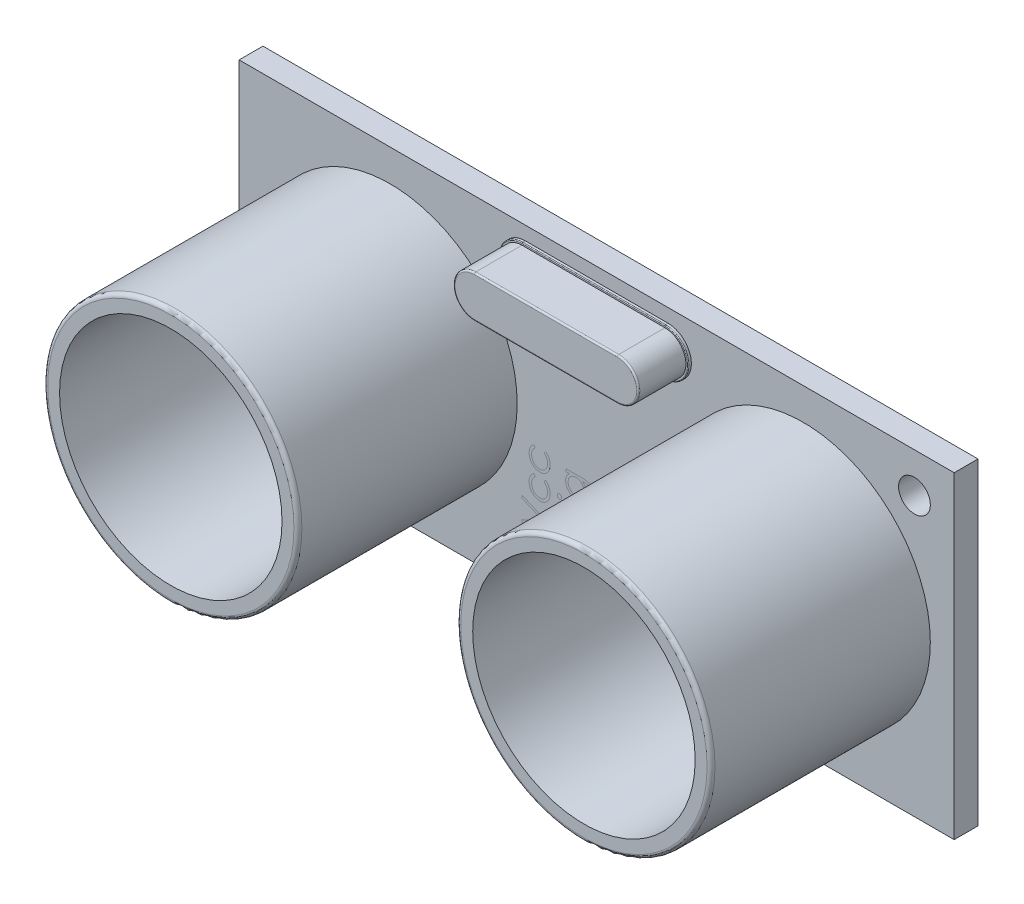
SolidWorks part; units mm, degrees
ref_plane "Front Plane" through (0, 0, 0) normal (0, 0, 1) x (1, 0, 0)
ref_plane "Top Plane" through (0, 0, 0) normal (0, 1, 0) x (1, 0, 0)
ref_plane "Right Plane" through (0, 0, 0) normal (1, 0, 0) x (0, 0, -1)
sketch "Sketch1" plane through (0, 0, 0) normal (0, 0, 1) x (1, 0, 0)
  line L1 (0, 0) -> (45, 0)
  line L2 (0, 0) -> (0, 20)
  line L3 (0, 20) -> (45, 20)
  line L4 (45, 0) -> (45, 20)
  circle A0 centre (2.5, 2.5) radius 1
  circle A1 centre (42.5, 17.5) radius 1
  dimension "D3" = 2
  dimension "D4" = 2
  dimension "D5" = 15
  dimension "D6" = 2.5
  dimension "D7" = 2.5
  dimension "D8" = 40
  dimension "D1" = 20
  dimension "D2" = 45
extrude "Boss-Extrude1" add sketch "Sketch1" along normal blind 1.5
sketch "Sketch2" plane through (0, 0, 1.5) normal (0, 0, 1) x (1, 0, 0)
  line L1 (45, 20) -> (0, 20) construction
  line L2 (22.5, 0) -> (22.5, 20) construction
  line L3 (0, 0) -> (45, 0) construction
  line L4 (22.5, 20) -> (22.5, 10) construction
  line L5 (22.5, 10) -> (35.5, 10) construction
  circle A0 centre (9.5, 10) radius 8
  circle A1 centre (35.5, 10) radius 8
  dimension "D1" = 16
  dimension "D2" = 16
  dimension "D3" = 13
  dimension "D5" = 10
  dimension "D6" = 10
  dimension "D7" = 13
extrude "Boss-Extrude2" add sketch "Sketch2" along normal blind 13.8
sketch "Sketch3" plane through (0, 0, 15.3) normal (0, 0, 1) x (1, 0, 0)
  circle A0 centre (9.5, 10) radius 7
  circle A1 centre (35.5, 10) radius 7
  circle A2 centre (35.5, 10) radius 8 construction
  dimension "D1" = 14
  dimension "D2" = 14
  dimension "D3" = 0
extrude "Cut-Extrude1" cut sketch "Sketch3" against normal blind 11
sketch "Sketch4" plane through (0, 0, 4.3) normal (0, 0, 1) x (1, 0, 0)
  circle A0 centre (9.5, 10) radius 6
  circle A1 centre (35.5, 10) radius 6
  circle A2 centre (35.5, 10) radius 7 construction
  dimension "D1" = 12
  dimension "D2" = 12
  dimension "D3" = 0
extrude "Boss-Extrude3" add sketch "Sketch4" along normal blind 1
fillet "Fillet1" radius 0.25 2 edges at (43.5, 10, 15.3) (17.5, 10, 15.3)
sketch "Sketch6" plane through (0, 0, 1.5) normal (0, 0, 1) x (1, 0, 0)
  line L0 (18.0118, 17.6702) -> (26.9882, 17.6702) construction
  line L1 (18.0118, 19.1439) -> (26.9882, 19.1439)
  line L2 (18.0118, 16.1964) -> (26.9882, 16.1964)
  line L3 (22.5, 20) -> (22.5, 17.6702) construction
  line L4 (45, 20) -> (0, 20) construction
  arc A0 (18.0118, 19.1439) -> (18.0118, 16.1964) centre (18.0118, 17.6702) ccw
  arc A1 (26.9882, 16.1964) -> (26.9882, 19.1439) centre (26.9882, 17.6702) ccw
  point P2 (22.5, 17.6702)
extrude "Boss-Extrude4" add sketch "Sketch6" along normal blind 0.2
sketch "Sketch7" plane through (0, 0, 1.7) normal (0, 0, 1) x (1, 0, 0)
  line L0 (18.001, 17.6795) -> (26.999, 17.6795) construction
  line L1 (18.001, 18.9989) -> (26.999, 18.9989)
  line L2 (18.001, 16.3602) -> (26.999, 16.3602)
  line L3 (0, 0) -> (45, 0) construction
  line L4 (45, 0) -> (22.5, 0) construction
  line L5 (22.5, 0) -> (22.5, 21.8843) construction
  arc A0 (18.001, 18.9989) -> (18.001, 16.3602) centre (18.001, 17.6795) ccw
  arc A1 (26.999, 16.3602) -> (26.999, 18.9989) centre (26.999, 17.6795) ccw
  point P2 (22.5, 17.6795)
  point P11 (22.5, 17.6795)
extrude "Boss-Extrude5" add sketch "Sketch7" along normal blind 3
fillet "Fillet2" radius 0.1 4 edges at (16.6817, 17.6795, 4.7) (22.5, 18.9989, 4.7) (28.3183, 17.6795, 4.7) (22.5, 16.3602, 4.7)
fillet "Fillet3" radius 0.05 4 edges at (28.462, 17.6702, 1.7) (22.5, 16.1964, 1.7) (16.538, 17.6702, 1.7) (22.5, 19.1439, 1.7)
sketch "Sketch9" plane through (0, 0, 0) normal (0, 0, -1) x (-1, 0, 0)
  line L1 (0, 0) -> (-45, 0) construction
  circle A0 centre (-26.31, 2.5) radius 0.635
  circle A1 centre (-23.77, 2.5) radius 0.635
  circle A2 centre (-21.23, 2.5) radius 0.635
  circle A3 centre (-18.69, 2.5) radius 0.635
  point P10 (-22.5, 0)
  dimension "D1" = 1.27
  dimension "D2" = 1.27
  dimension "D3" = 1.27
  dimension "D4" = 1.27
  dimension "D5" = 2.5
  dimension "D6" = 2.54
  dimension "D7" = 2.54
  dimension "D8" = 2.54
  dimension "D9" = 2.5
  dimension "D10" = 2.5
  dimension "D11" = 2.5
  dimension "D12" = 1.27
extrude "Boss-Extrude6" add sketch "Sketch9" along normal blind 4 and the other way blind 2
sketch "Sketch10" plane through (0, 0, 1.5) normal (0, 0, 1) x (1, 0, 0)
  line L0 (19.5534, 3.5859) -> (19.5534, 8.1823) construction
  line L1 (21.8515, 8.1823) -> (21.8515, 3.5859) construction
  line L2 (24.4945, 8.1823) -> (24.4945, 3.5859) construction
  line L3 (27.0991, 8.1823) -> (27.0991, 3.5859) construction
  text T0 "Vcc" font "Century Gothic" height 1.75
  text T1 "Trig" font "Century Gothic" height 1.75
  text T2 "Echo" font "Century Gothic" height 1.75
  text T3 "GND" font "Century Gothic" height 1.75
extrude "Boss-Extrude7" add sketch "Sketch10" along normal blind 0.0001
